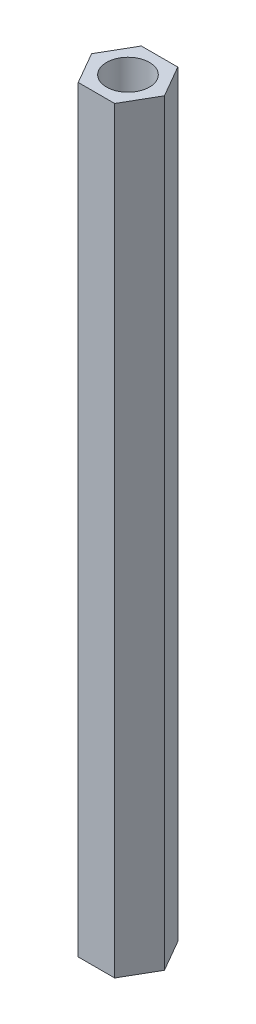
SolidWorks part; units mm, degrees
material "黄铜"
ref_plane "前视基准面" through (0, 0, 0) normal (0, 0, 1) x (1, 0, 0)
ref_plane "上视基准面" through (0, 0, 0) normal (0, 1, 0) x (1, 0, 0)
ref_plane "右视基准面" through (0, 0, 0) normal (1, 0, 0) x (0, 0, -1)
sketch "草图1" plane through (0, 0, 0) normal (0, 1, 0) x (1, 0, 0)
  line L1 (2.8868, 0) -> (1.4434, 2.5)
  line L2 (1.4434, 2.5) -> (-1.4434, 2.5)
  line L3 (-1.4434, 2.5) -> (-2.8868, 0)
  line L4 (-2.8868, 0) -> (-1.4434, -2.5)
  line L5 (-1.4434, -2.5) -> (1.4434, -2.5)
  line L6 (1.4434, -2.5) -> (2.8868, 0)
  circle A0 centre (0, 0) radius 1.7
  circle A1 centre (0, 0) radius 2.5 construction
  dimension "D1" = 3.4
  dimension "D2" = 5
extrude "凸台-拉伸1" add sketch "草图1" along normal blind 60
equation "\"h\" = 60'铜柱的长度"
equation "\"D1@凸台-拉伸1\"=\"h\""
equation "\"d\"= 3'螺丝直径(有补偿)"
equation "\"D1@草图1\"=\"d\"+0.4"
